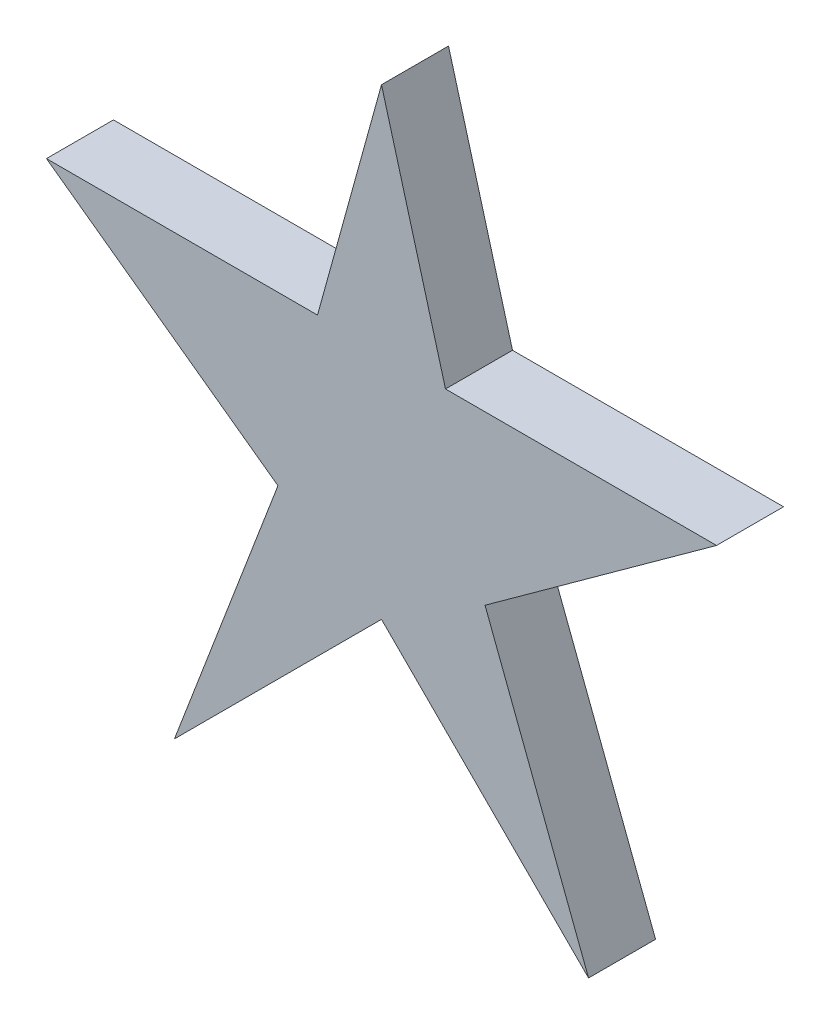
SolidWorks part; units mm, degrees
ref_plane "前视基准面" through (0, 0, 0) normal (0, 0, 1) x (1, 0, 0)
ref_plane "上视基准面" through (0, 0, 0) normal (0, 1, 0) x (1, 0, 0)
ref_plane "右视基准面" through (0, 0, 0) normal (1, 0, 0) x (0, 0, -1)
other "Configuration Table"
sketch "草图1" plane through (0, 0, 0) normal (0, 0, 1) x (1, 0, 0)
  line L0 (0, 500) -> (95.5, 154.5)
  line L1 (95.5, 154.5) -> (500, 154.5)
  line L2 (500, 154.5) -> (154.5, -95.5)
  line L3 (154.5, -95.5) -> (309, -500)
  line L4 (309, -500) -> (0, -191)
  line L5 (0, -191) -> (-309, -500)
  line L6 (-309, -500) -> (-154.5, -95.5)
  line L7 (-154.5, -95.5) -> (-500, 154.5)
  line L8 (-500, 154.5) -> (-95.5, 154.5)
  line L9 (-95.5, 154.5) -> (0, 500)
extrude "凸台-拉伸1" add sketch "草图1" along normal blind 100
